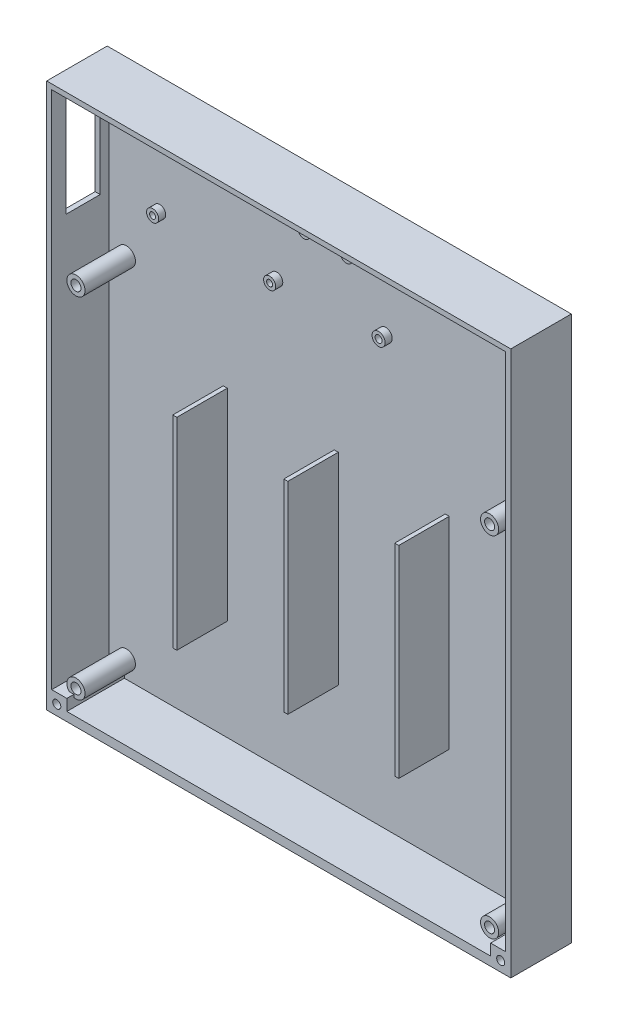
SolidWorks part; units mm, degrees
ref_plane "Plan de face" through (0, 0, 0) normal (0, 0, 1) x (1, 0, 0)
ref_plane "Plan de dessus" through (0, 0, 0) normal (0, 1, 0) x (1, 0, 0)
ref_plane "Plan de droite" through (0, 0, 0) normal (1, 0, 0) x (0, 0, -1)
sketch "Esquisse1" plane through (0, 0, 0) normal (0, 0, 1) x (1, 0, 0)
  line L0 (0, 136.5625) -> (0, -142.8125) construction
  line L1 (-195, -41.5625) -> (201.25, -41.5625) construction
  line L2 (115, 93.4375) -> (-115, 93.4375)
  line L3 (-115, 93.4375) -> (-115, -176.5625)
  line L4 (115, -176.5625) -> (-115, -176.5625)
  line L6 (115, 93.4375) -> (115, -176.5625)
  point P10 (-115, -41.5625)
  point P12 (0, 93.4375)
  dimension "D1" = 115
  dimension "D2" = 135
extrude "Boss.-Extru.1" add sketch "Esquisse1" along normal blind 5
sketch "Esquisse2" plane through (0, 0, 5) normal (0, 0, 1) x (1, 0, 0)
  line L0 (-115, -176.5625) -> (115, -176.5625) construction
  line L1 (-115, 93.4375) -> (-115, -176.5625) construction
  line L2 (-1.5, 152.9836) -> (-1.5, -221.0762) construction
  line L3 (-154.951, -77.0625) -> (207.3243, -77.0625) construction
  line L4 (115, 93.4375) -> (-115, 93.4375) construction
  line L5 (115, -176.5625) -> (115, 93.4375) construction
  line L6 (152.1134, 61.4375) -> (-165.3137, 61.4375) construction
  line L7 (-58.5, 134.3556) -> (-58.5, 23.9251) construction
  line L8 (-25.2083, 61.4375) -> (-76.5448, 61.4375) construction
  line L9 (-2, 113.0864) -> (-2, 66.437) construction
  line L10 (-19.2346, 73.6875) -> (13.2189, 73.6875) construction
  circle A0 centre (-104, -163.5625) radius 2
  circle A7 centre (-104, 9.4375) radius 2
  circle A8 centre (104.5, 82.9375) radius 1.75
  circle A9 centre (24.5, 82.9375) radius 1.75
  circle A10 centre (24.5, 39.9375) radius 1.75
  circle A11 centre (104.5, 39.9375) radius 1.75
  circle A12 centre (-87.5, 85.9375) radius 1.5
  circle A13 centre (-29.5, 85.9375) radius 1.5
  circle A116 centre (8.5, 67.4375) radius 1.5
  circle A117 centre (-12.5, 67.4375) radius 1.5
  circle A118 centre (-12.5, 79.9375) radius 1.5
  circle A119 centre (8.5, 79.9375) radius 1.5
  circle A120 centre (101, -163.5625) radius 2
  circle A121 centre (101, 9.4375) radius 2
  circle A122 centre (-87.5, 36.9375) radius 1.5
  circle A123 centre (-29.5, 36.9375) radius 1.5
  dimension "D1" = 4
  dimension "D4" = 26
  dimension "D10" = 3.5
  dimension "D11" = 3.5
  dimension "D13" = 3
  dimension "D17" = 24.5
  dimension "D21" = 10.5
  dimension "D22" = 3
  dimension "D20" = 102.5
  dimension "D2" = 13
  dimension "D3" = 11
  dimension "D5" = 86.5
  dimension "D6" = 10.5
  dimension "D7" = 10.5
  dimension "D8" = 10.5
  dimension "D9" = 80
  dimension "D12" = 21.5
  dimension "D14" = 27.5
  dimension "D15" = 7.5
  dimension "D16" = 29
  dimension "D23" = 6.25
extrude "Enlèv. mat.-Extru.1" cut sketch "Esquisse2" against normal blind 5
shell "Coque3" thickness 1.5
sketch "Esquisse3" plane through (0, 0, 1.5) normal (0, 0, 1) x (1, 0, 0)
  line L0 (-1.5, 104.4372) -> (-1.5, -196.0583) construction
  line L1 (104, -77.0625) -> (-172.0752, -77.0625) construction
  circle A0 centre (-104, 9.4375) radius 4.5
  circle A4 centre (-104, -163.5625) radius 4.5
  circle A5 centre (-104, 9.4375) radius 2.5
  circle A6 centre (-104, -163.5625) radius 2.5
  circle A8 centre (101, -163.5625) radius 4.5
  circle A9 centre (101, -163.5625) radius 2.5
  circle A10 centre (101, 9.4375) radius 4.5
  circle A11 centre (101, 9.4375) radius 2.5
  dimension "D1" = 9
  dimension "D2" = 5
  dimension "D4" = 102.5
  dimension "D3" = 86.5
extrude "Boss.-Extru.3" add sketch "Esquisse3" along normal blind 25
sketch "Esquisse4" plane through (0, 0, 1.5) normal (0, 0, 1) x (1, 0, 0)
  line L0 (-113.5, -175.0625) -> (113.5, -175.0625) construction
  line L1 (-113.5, 91.9375) -> (-112.5, 91.9375)
  line L2 (-113.5, 91.9375) -> (-113.5, -175.0625)
  line L3 (-113.5, -175.0625) -> (-112.5, -175.0625)
  line L4 (-112.5, 91.9375) -> (-112.5, -175.0625)
  line L5 (0, 95.4885) -> (0, -188.2553) construction
  line L6 (113.5, -175.0625) -> (112.5, -175.0625)
  line L7 (113.5, 91.9375) -> (113.5, -175.0625)
  line L8 (113.5, 91.9375) -> (112.5, 91.9375)
  line L9 (112.5, 91.9375) -> (112.5, -175.0625)
  dimension "D1" = 1
extrude "Boss.-Extru.4" add sketch "Esquisse4" along normal blind 3.5
sketch "Esquisse5" plane through (0, 0, 1.5) normal (0, 0, 1) x (1, 0, 0)
  line L0 (112.5, 91.9375) -> (112.5, -175.0625) construction
  line L1 (-112.5, 91.9375) -> (112.5, 91.9375)
  line L2 (-112.5, 91.9375) -> (-112.5, 90.9375)
  line L3 (-112.5, 90.9375) -> (112.5, 90.9375)
  line L4 (112.5, 91.9375) -> (112.5, 90.9375)
  line L5 (-112.5, -175.0625) -> (-112.5, 91.9375) construction
  line L6 (-196.2712, -42.5625) -> (155.2477, -42.5625) construction
  line L7 (-112.5, -172.1625) -> (112.5, -172.1625)
  line L8 (-112.5, -172.1625) -> (-112.5, -175.0625)
  line L9 (-112.5, -175.0625) -> (112.5, -175.0625)
  line L10 (112.5, -172.1625) -> (112.5, -175.0625)
  dimension "D1" = 1
  dimension "D2" = 133.5
  dimension "D3" = 2.9
extrude "Boss.-Extru.10" add sketch "Esquisse5" along normal blind 3.5
sketch "Esquisse7" plane through (0, 0, 1.5) normal (0, 0, 1) x (1, 0, 0)
  line L0 (1, -22.1625) -> (1, -122.1625)
  line L5 (-1, -22.1625) -> (1, -22.1625)
  line L6 (-151.213, -61.5625) -> (245.9243, -61.5625) construction
  line L57 (-1, -22.1625) -> (-1, -122.1625)
  line L58 (-56, -22.1625) -> (-54, -22.1625)
  line L59 (-56, -22.1625) -> (-56, -122.1625)
  line L60 (-56, -122.1625) -> (-54, -122.1625)
  line L61 (-54, -22.1625) -> (-54, -122.1625)
  line L62 (-1, -122.1625) -> (1, -122.1625)
  line L63 (56, -22.1625) -> (56, -122.1625)
  line L64 (54, -22.1625) -> (56, -22.1625)
  line L65 (54, -22.1625) -> (54, -122.1625)
  line L66 (54, -122.1625) -> (56, -122.1625)
  line L67 (-112.5, -172.1625) -> (-112.5, 90.9375) construction
  line L68 (112.5, -172.1625) -> (-112.5, -172.1625) construction
  dimension "D1" = 2
  dimension "D2" = 100
  dimension "D3" = 3
  dimension "D4" = 56.5
  dimension "D5" = 50
extrude "Boss.-Extru.11" add sketch "Esquisse7" along normal blind 25
sketch "Esquisse8" plane through (0, 0, 5) normal (0, 0, 1) x (1, 0, 0)
  line L0 (-112.5, 90.9375) -> (-112.5, -172.1625)
  line L1 (-112.5, -172.1625) -> (112.5, -172.1625)
  line L2 (112.5, -172.1625) -> (112.5, 90.9375)
  line L3 (112.5, 90.9375) -> (-112.5, 90.9375)
  line L4 (-115, 93.4375) -> (-115, -176.5625)
  line L5 (-115, -176.5625) -> (115, -176.5625)
  line L6 (115, -176.5625) -> (115, 93.4375)
  line L7 (115, 93.4375) -> (-115, 93.4375)
extrude "Boss.-Extru.12" add sketch "Esquisse8" along normal blind 25
sketch "Esquisse13" plane through (-112.5, 0, 0) normal (1, 0, 0) x (0, 0, -1)
  line L2 (-23, 88.9375) -> (-23, 33.9375)
  line L6 (-30, 93.4375) -> (-30, -176.5625) construction
  line L8 (-23, 88.9375) -> (-6, 88.9375)
  line L9 (-6, 88.9375) -> (-6, 33.9375)
  line L10 (-6, 33.9375) -> (-23, 33.9375)
  line L11 (-30, 93.4375) -> (0, 93.4375) construction
  line L12 (0, 93.4375) -> (0, -176.5625) construction
  dimension "D1" = 4.5
  dimension "D2" = 55
  dimension "D3" = 7
  dimension "D4" = 6
extrude "Enlèv. mat.-Extru.4" cut sketch "Esquisse13" against normal blind 10
sketch "Esquisse16" plane through (0, 0, 1.5) normal (0, 0, 1) x (1, 0, 0)
  line L0 (0, 132.0412) -> (0, -334.7684) construction
  line L1 (-112.5, -172.1625) -> (-105, -172.1625)
  line L2 (-112.5, -172.1625) -> (-112.5, -166.5625)
  line L3 (-112.5, -166.5625) -> (-105, -166.5625)
  line L4 (-105, -172.1625) -> (-105, -166.5625)
  line L5 (112.5, -172.1625) -> (112.5, -166.5625)
  line L6 (112.5, -166.5625) -> (105, -166.5625)
  line L7 (105, -172.1625) -> (105, -166.5625)
  line L8 (112.5, -172.1625) -> (105, -172.1625)
  dimension "D1" = 5.6
  dimension "D2" = 7.5
extrude "Boss.-Extru.13" add sketch "Esquisse16" along normal blind 28.5
sketch "Esquisse17" plane through (0, 0, 30) normal (0, 0, 1) x (1, 0, 0)
  line L0 (-105, -166.5625) -> (-112.5, -166.5625) construction
  line L1 (-105, -172.1625) -> (-105, -166.5625) construction
  line L2 (0, 131.6663) -> (0, -232.3365) construction
  circle A0 centre (-110, -171.5625) radius 2
  circle A1 centre (110, -171.5625) radius 2
  dimension "D1" = 4
  dimension "D2" = 5
  dimension "D3" = 5
extrude "Enlèv. mat.-Extru.5" cut sketch "Esquisse17" against normal through all
